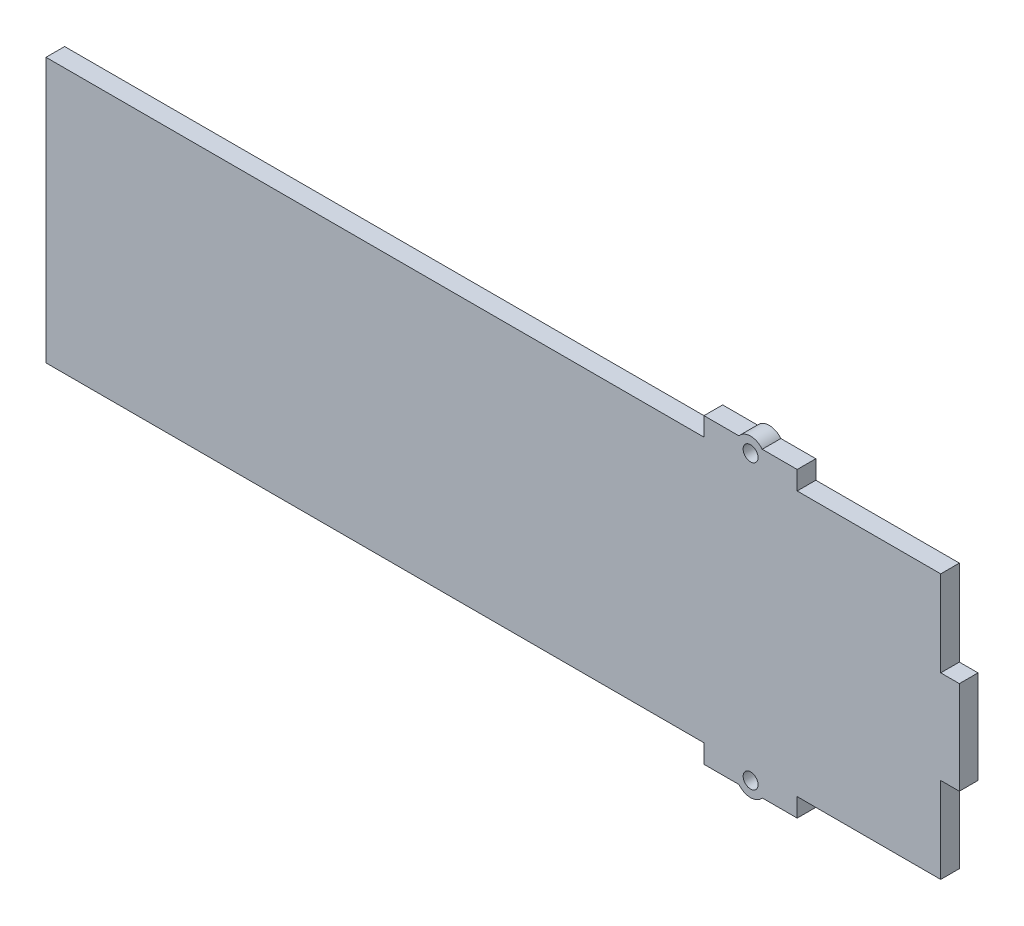
SolidWorks part; units mm, degrees
ref_plane "Front Plane" through (0, 0, 0) normal (0, 0, 1) x (1, 0, 0)
ref_plane "Top Plane" through (0, 0, 0) normal (0, 1, 0) x (1, 0, 0)
ref_plane "Right Plane" through (0, 0, 0) normal (1, 0, 0) x (0, 0, -1)
sketch "Sketch1" plane through (0, 0, 0) normal (0, 0, 1) x (1, 0, 0)
  line L1 (-51, 35.5) -> (51, 35.5)
  line L2 (-51, 35.5) -> (-51, -35.5)
  line L3 (-51, -35.5) -> (51, -35.5)
  line L4 (51, 35.5) -> (51, -35.5)
  dimension "D1" = 102
  dimension "D2" = 71
  dimension "D3" = 51
  dimension "D4" = 35.5
extrude "Boss-Extrude1" add sketch "Sketch1" along normal blind 5
sketch "Sketch3" plane through (0, 0, 5) normal (0, 0, 1) x (1, 0, 0)
  line L0 (51, 35.5) -> (-51, 35.5) construction
  line L1 (-12.5, 35.5) -> (12.5, 35.5)
  line L2 (-12.5, 35.5) -> (-12.5, 40.5)
  line L3 (-12.5, 40.5) -> (12.5, 40.5)
  line L4 (12.5, 35.5) -> (12.5, 40.5)
  line L5 (-51, 35.5) -> (-51, -35.5) construction
  line L6 (51, 12.5) -> (56, 12.5)
  line L7 (51, -35.5) -> (51, 35.5) construction
  line L8 (56, 12.5) -> (56, -12.5)
  line L9 (56, -12.5) -> (51, -12.5)
  line L10 (51, -12.5) -> (51, 12.5)
  line L11 (-51, -35.5) -> (51, -35.5) construction
  line L12 (-51, -35.5) -> (51, -35.5) construction
  line L13 (12.5, -35.5) -> (-12.5, -35.5)
  line L14 (12.5, -35.5) -> (12.5, -40.5)
  line L15 (12.5, -40.5) -> (-12.5, -40.5)
  line L16 (-12.5, -35.5) -> (-12.5, -40.5)
  dimension "D1" = 5
  dimension "D2" = 38.5
  dimension "D3" = 25
  dimension "D4" = 5
  dimension "D5" = 25
  dimension "D6" = 23
  dimension "D7" = 5
extrude "Boss-Extrude2" add sketch "Sketch3" against normal blind 5
sketch "Sketch4" plane through (0, 0, 5) normal (0, 0, 1) x (1, 0, 0)
  line L0 (12.5, 40.5) -> (-12.5, 40.5) construction
  line L1 (-12.5, -40.5) -> (12.5, -40.5) construction
  line L2 (-12.5, 40.5) -> (-12.5, 35.5) construction
  line L3 (-12.5, -35.5) -> (-12.5, -40.5) construction
  circle A0 centre (0, 38) radius 2
  circle A1 centre (0, -38) radius 2
  dimension "D1" = 4
  dimension "D2" = 4
  dimension "D3" = 2.5
  dimension "D4" = 2.5
  dimension "D5" = 12.5
  dimension "D6" = 12.5
extrude "Cut-Extrude1" cut sketch "Sketch4" against normal blind 5
sketch "Sketch5" plane through (0, 0, 5) normal (0, 0, 1) x (1, 0, 0)
  circle A0 centre (0, 38) radius 2
  circle A1 centre (0, 38) radius 4
  circle A2 centre (0, -38) radius 2
  circle A3 centre (0, -38) radius 4
  dimension "D1" = 8
  dimension "D2" = 8
  dimension "D3" = 4
  dimension "D4" = 4
extrude "Boss-Extrude3" add sketch "Sketch5" against normal blind 5
sketch "Sketch6" plane through (0, 0, 5) normal (0, 0, 1) x (1, 0, 0)
  line L0 (-51, -35.5) -> (-12.5, -35.5) construction
  line L1 (-51, 35.5) -> (-189, 35.5)
  line L2 (-51, 35.5) -> (-51, -35.5)
  line L3 (-51, -35.5) -> (-189, -35.5)
  line L4 (-189, 35.5) -> (-189, -35.5)
  dimension "D1" = 138
extrude "Boss-Extrude4" add sketch "Sketch6" against normal blind 5
